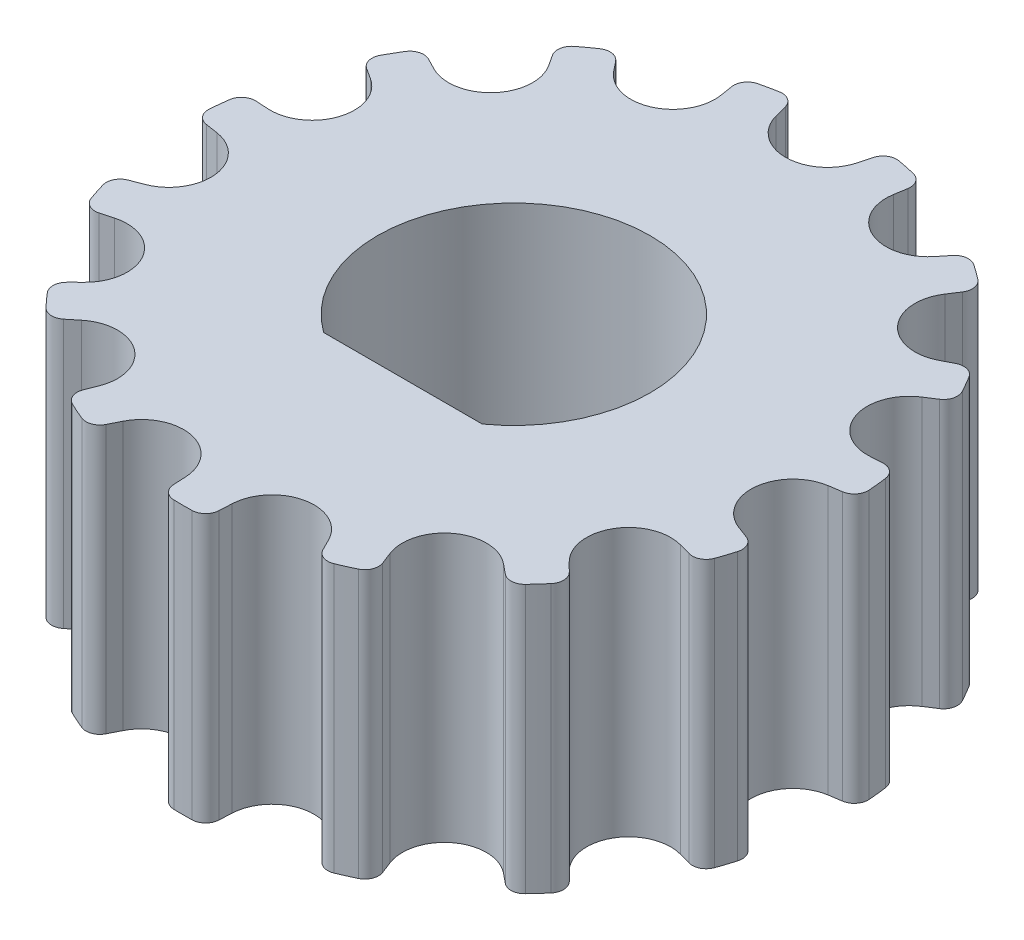
SolidWorks part; units mm, degrees
material "Acrylic (Medium-high impact)"
ref_plane "Front Plane" through (0, 0, 0) normal (0, 0, 1) x (1, 0, 0)
ref_plane "Top Plane" through (0, 0, 0) normal (0, 1, 0) x (1, 0, 0)
ref_plane "Right Plane" through (0, 0, 0) normal (1, 0, 0) x (0, 0, -1)
sketch "Sketch1" plane through (0, 0, 0) normal (0, 1, 0) x (1, 0, 0)
  circle A0 centre (0, 0) radius 7.162
  dimension "D1" = 14.3239
extrude "Boss-Extrude1" add sketch "Sketch1" along normal blind 5.8
sketch "Sketch2" plane through (0, 5.8, 0) normal (0, 1, 0) x (1, 0, 0)
  line L0 (0, 0) -> (0, 7.162) construction
  line L1 (-0.8799, 6.5598) -> (-0.95, 6.8255)
  line L2 (-2.913, 6.5428) -> (-2.913, 7.162)
  line L3 (-2.913, 7.162) -> (2.913, 7.162)
  line L4 (0.8799, 6.5598) -> (0.95, 6.8255)
  line L5 (2.913, 6.5428) -> (2.913, 7.162)
  circle A0 centre (0, 0) radius 7.162 construction
  arc A1 (0.8799, 6.5598) -> (-0.8799, 6.5598) centre (0, 6.792) cw
  arc A2 (-0.95, 6.8255) -> (-1.2943, 7.0441) centre (-1.2401, 6.749) ccw
  arc A4 (0.95, 6.8255) -> (1.2943, 7.0441) centre (1.2401, 6.749) cw
  arc A5 (-1.2943, 7.0441) -> (-2.913, 6.5428) centre (0, 0) ccw
  arc A6 (1.2943, 7.0441) -> (2.913, 6.5428) centre (0, 0) cw
  point P11 (0, 7.162)
  point P19 (0, 5.882)
  dimension "D3" = 0.3
  dimension "D5" = 0.91
  dimension "D2" = 0.95
  dimension "D4" = 1.28
  dimension "D6" = 24
extrude "Cut-Extrude1" cut sketch "Sketch2" against normal through all
pattern_circular "CirPattern1" count 15 over 360 about axis through (0, 0, 0) along (0, 1, 0) of "Cut-Extrude1"
sketch "Sketch3" plane through (0, 0, 0) normal (0, -1, 0) x (1, 0, 0)
  line L0 (1.7154, 2.4) -> (-1.7154, 2.4)
  arc A0 (-1.7154, 2.4) -> (1.7154, 2.4) centre (0, 0) ccw
  dimension "D1" = 5.9
  dimension "D2" = 2.4
extrude "Cut-Extrude2" cut sketch "Sketch3" against normal through all
sketch "Sketch5" plane through (0, 0, 0) normal (0, -1, 0) x (1, 0, 0)
  line L60 (5.4179, -3.8244) -> (5.6623, -3.9501)
  line L61 (6.252, -2.9286) -> (6.021, -2.7798)
  line L62 (6.505, -1.2901) -> (6.7794, -1.3055)
  line L63 (6.9027, -0.1325) -> (6.6311, -0.0906)
  line L64 (6.4674, 1.4673) -> (6.7243, 1.5648)
  line L65 (6.3598, 2.6865) -> (6.0946, 2.6144)
  line L66 (5.3115, 3.9709) -> (5.5065, 4.1645)
  line L67 (4.7173, 5.041) -> (4.5044, 4.8673)
  line L68 (3.2371, 5.788) -> (3.3366, 6.0442)
  line L69 (2.2591, 6.5239) -> (2.1352, 6.2786)
  line L70 (0.6031, 6.6042) -> (0.5897, 6.8787)
  line L71 (-0.5897, 6.8787) -> (-0.6031, 6.6042)
  line L72 (-2.1352, 6.2786) -> (-2.2591, 6.5239)
  line L73 (-3.3366, 6.0442) -> (-3.2371, 5.788)
  line L74 (-4.5044, 4.8673) -> (-4.7173, 5.041)
  line L75 (-5.5065, 4.1645) -> (-5.3115, 3.9709)
  line L76 (-6.0946, 2.6144) -> (-6.3598, 2.6865)
  line L77 (-6.7243, 1.5648) -> (-6.4674, 1.4673)
  line L78 (-6.6311, -0.0906) -> (-6.9027, -0.1325)
  line L79 (-6.7794, -1.3055) -> (-6.505, -1.2901)
  line L80 (-6.021, -2.7798) -> (-6.252, -2.9286)
  line L81 (-5.6623, -3.9501) -> (-5.4179, -3.8244)
  line L82 (-4.3698, -4.9885) -> (-4.5203, -5.2184)
  line L83 (-3.5661, -5.9117) -> (-3.394, -5.6974)
  line L84 (-1.963, -6.3345) -> (-2.007, -6.6058)
  line L85 (-0.8533, -6.851) -> (-0.7832, -6.5853)
  line L86 (0.7832, -6.5853) -> (0.8533, -6.851)
  line L87 (2.007, -6.6058) -> (1.963, -6.3345)
  line L88 (3.394, -5.6974) -> (3.5661, -5.9117)
  line L89 (4.5203, -5.2184) -> (4.3698, -4.9885)
  line L90 (5.4179, -3.8244) -> (5.6623, -3.9501)
  line L91 (6.252, -2.9286) -> (6.021, -2.7798)
  line L92 (6.505, -1.2901) -> (6.7794, -1.3055)
  line L93 (6.9027, -0.1325) -> (6.6311, -0.0906)
  line L94 (6.4674, 1.4673) -> (6.7243, 1.5648)
  line L95 (6.3598, 2.6865) -> (6.0946, 2.6144)
  line L96 (5.3115, 3.9709) -> (5.5065, 4.1645)
  line L97 (4.7173, 5.041) -> (4.5044, 4.8673)
  line L98 (3.2371, 5.788) -> (3.3366, 6.0442)
  line L99 (2.2591, 6.5239) -> (2.1352, 6.2786)
  line L100 (0.6031, 6.6042) -> (0.5897, 6.8787)
  line L101 (-0.5897, 6.8787) -> (-0.6031, 6.6042)
  line L102 (-2.1352, 6.2786) -> (-2.2591, 6.5239)
  line L103 (-3.3366, 6.0442) -> (-3.2371, 5.788)
  line L104 (-4.5044, 4.8673) -> (-4.7173, 5.041)
  line L105 (-5.5065, 4.1645) -> (-5.3115, 3.9709)
  line L106 (-6.0946, 2.6144) -> (-6.3598, 2.6865)
  line L107 (-6.7243, 1.5648) -> (-6.4674, 1.4673)
  line L108 (-6.6311, -0.0906) -> (-6.9027, -0.1325)
  line L109 (-6.7794, -1.3055) -> (-6.505, -1.2901)
  line L110 (-6.021, -2.7798) -> (-6.252, -2.9286)
  line L111 (-5.6623, -3.9501) -> (-5.4179, -3.8244)
  line L112 (-4.3698, -4.9885) -> (-4.5203, -5.2184)
  line L113 (-3.5661, -5.9117) -> (-3.394, -5.6974)
  line L114 (-1.963, -6.3345) -> (-2.007, -6.6058)
  line L115 (-0.8533, -6.851) -> (-0.7832, -6.5853)
  line L116 (0.7832, -6.5853) -> (0.8533, -6.851)
  line L117 (2.007, -6.6058) -> (1.963, -6.3345)
  line L118 (3.394, -5.6974) -> (3.5661, -5.9117)
  line L119 (4.5203, -5.2184) -> (4.3698, -4.9885)
  circle A60 centre (0, 0) radius 3.9038
  arc A120 (5.6623, -3.9501) -> (6.186, -3.8039) centre (5.8452, -3.5944) ccw
  arc A121 (6.186, -3.8039) -> (6.3873, -3.4553) centre (0, 0) ccw
  arc A122 (6.3873, -3.4553) -> (6.252, -2.9286) centre (6.0355, -3.2649) ccw
  arc A123 (6.505, -1.2901) -> (6.021, -2.7798) centre (6.4595, -2.0988) ccw
  arc A124 (6.7794, -1.3055) -> (7.1984, -0.959) centre (6.8019, -0.9062) ccw
  arc A125 (7.1984, -0.959) -> (7.2405, -0.5586) centre (0, 0) ccw
  arc A126 (7.2405, -0.5586) -> (6.9027, -0.1325) centre (6.8416, -0.5278) ccw
  arc A127 (6.4674, 1.4673) -> (6.6311, -0.0906) centre (6.7548, 0.71) ccw
  arc A128 (6.7243, 1.5648) -> (6.9661, 2.0518) centre (6.5824, 1.9387) ccw
  arc A129 (6.9661, 2.0518) -> (6.8417, 2.4347) centre (0, 0) ccw
  arc A130 (6.8417, 2.4347) -> (6.3598, 2.6865) centre (6.4648, 2.3006) ccw
  arc A131 (5.3115, 3.9709) -> (6.0946, 2.6144) centre (5.882, 3.396) ccw
  arc A132 (5.5065, 4.1645) -> (5.5293, 4.7077) centre (5.2248, 4.4484) ccw
  arc A133 (5.5293, 4.7077) -> (5.2599, 5.0069) centre (0, 0) ccw
  arc A134 (5.2599, 5.0069) -> (4.7173, 5.041) centre (4.9702, 4.7312) ccw
  arc A135 (3.2371, 5.788) -> (4.5044, 4.8673) centre (3.9922, 5.4948) ccw
  arc A136 (3.3366, 6.0442) -> (3.1365, 6.5497) centre (2.9637, 6.1889) ccw
  arc A137 (3.1365, 6.5497) -> (2.7687, 6.7135) centre (0, 0) ccw
  arc A138 (2.7687, 6.7135) -> (2.2591, 6.5239) centre (2.6162, 6.3437) ccw
  arc A139 (0.6031, 6.6042) -> (2.1352, 6.2786) centre (1.4121, 6.6436) ccw
  arc A140 (0.5897, 6.8787) -> (0.2013, 7.2592) centre (0.1902, 6.8593) ccw
  arc A141 (0.2013, 7.2592) -> (-0.2013, 7.2592) centre (0, 0) ccw
  arc A142 (-0.2013, 7.2592) -> (-0.5897, 6.8787) centre (-0.1902, 6.8593) ccw
  arc A143 (-2.1352, 6.2786) -> (-0.6031, 6.6042) centre (-1.4121, 6.6436) ccw
  arc A144 (-2.2591, 6.5239) -> (-2.7687, 6.7135) centre (-2.6162, 6.3437) ccw
  arc A145 (-2.7687, 6.7135) -> (-3.1365, 6.5497) centre (0, 0) ccw
  arc A146 (-3.1365, 6.5497) -> (-3.3366, 6.0442) centre (-2.9637, 6.1889) ccw
  arc A147 (-4.5044, 4.8673) -> (-3.2371, 5.788) centre (-3.9922, 5.4948) ccw
  arc A148 (-4.7173, 5.041) -> (-5.2599, 5.0069) centre (-4.9702, 4.7312) ccw
  arc A149 (-5.2599, 5.0069) -> (-5.5293, 4.7077) centre (0, 0) ccw
  arc A150 (-5.5293, 4.7077) -> (-5.5065, 4.1645) centre (-5.2248, 4.4484) ccw
  arc A151 (-6.0946, 2.6144) -> (-5.3115, 3.9709) centre (-5.882, 3.396) ccw
  arc A152 (-6.3598, 2.6865) -> (-6.8417, 2.4347) centre (-6.4648, 2.3006) ccw
  arc A153 (-6.8417, 2.4347) -> (-6.9661, 2.0518) centre (0, 0) ccw
  arc A154 (-6.9661, 2.0518) -> (-6.7243, 1.5648) centre (-6.5824, 1.9387) ccw
  arc A155 (-6.6311, -0.0906) -> (-6.4674, 1.4673) centre (-6.7548, 0.71) ccw
  arc A156 (-6.9027, -0.1325) -> (-7.2405, -0.5586) centre (-6.8416, -0.5278) ccw
  arc A157 (-7.2405, -0.5586) -> (-7.1984, -0.959) centre (0, 0) ccw
  arc A158 (-7.1984, -0.959) -> (-6.7794, -1.3055) centre (-6.8019, -0.9062) ccw
  arc A159 (-6.021, -2.7798) -> (-6.505, -1.2901) centre (-6.4595, -2.0988) ccw
  arc A160 (-6.252, -2.9286) -> (-6.3873, -3.4553) centre (-6.0355, -3.2649) ccw
  arc A161 (-6.3873, -3.4553) -> (-6.186, -3.8039) centre (0, 0) ccw
  arc A162 (-6.186, -3.8039) -> (-5.6623, -3.9501) centre (-5.8452, -3.5944) ccw
  arc A163 (-4.3698, -4.9885) -> (-5.4179, -3.8244) centre (-5.0474, -4.5447) ccw
  arc A164 (-4.5203, -5.2184) -> (-4.4297, -5.7545) centre (-4.1857, -5.4375) ccw
  arc A165 (-4.4297, -5.7545) -> (-4.104, -5.9911) centre (0, 0) ccw
  arc A166 (-4.104, -5.9911) -> (-3.5661, -5.9117) centre (-3.8779, -5.6611) ccw
  arc A167 (-1.963, -6.3345) -> (-3.394, -5.6974) centre (-2.7625, -6.2048) ccw
  arc A168 (-2.007, -6.6058) -> (-1.7062, -7.0587) centre (-1.6122, -6.6699) ccw
  arc A169 (-1.7062, -7.0587) -> (-1.3124, -7.1424) centre (0, 0) ccw
  arc A170 (-1.3124, -7.1424) -> (-0.8533, -6.851) centre (-1.2401, -6.749) ccw
  arc A171 (0.7832, -6.5853) -> (-0.7832, -6.5853) centre (0, -6.792) ccw
  arc A172 (0.8533, -6.851) -> (1.3124, -7.1424) centre (1.2401, -6.749) ccw
  arc A173 (1.3124, -7.1424) -> (1.7062, -7.0587) centre (0, 0) ccw
  arc A174 (1.7062, -7.0587) -> (2.007, -6.6058) centre (1.6122, -6.6699) ccw
  arc A175 (3.394, -5.6974) -> (1.963, -6.3345) centre (2.7625, -6.2048) ccw
  arc A176 (3.5661, -5.9117) -> (4.104, -5.9911) centre (3.8779, -5.6611) ccw
  arc A177 (4.104, -5.9911) -> (4.4297, -5.7545) centre (0, 0) ccw
  arc A178 (4.4297, -5.7545) -> (4.5203, -5.2184) centre (4.1857, -5.4375) ccw
  arc A179 (5.4179, -3.8244) -> (4.3698, -4.9885) centre (5.0474, -4.5447) ccw
  arc A180 (5.6623, -3.9501) -> (6.186, -3.8039) centre (5.8452, -3.5944) ccw
  arc A181 (6.186, -3.8039) -> (6.3873, -3.4553) centre (0, 0) ccw
  arc A182 (6.3873, -3.4553) -> (6.252, -2.9286) centre (6.0355, -3.2649) ccw
  arc A183 (6.505, -1.2901) -> (6.021, -2.7798) centre (6.4595, -2.0988) ccw
  arc A184 (6.7794, -1.3055) -> (7.1984, -0.959) centre (6.8019, -0.9062) ccw
  arc A185 (7.1984, -0.959) -> (7.2405, -0.5586) centre (0, 0) ccw
  arc A186 (7.2405, -0.5586) -> (6.9027, -0.1325) centre (6.8416, -0.5278) ccw
  arc A187 (6.4674, 1.4673) -> (6.6311, -0.0906) centre (6.7548, 0.71) ccw
  arc A188 (6.7243, 1.5648) -> (6.9661, 2.0518) centre (6.5824, 1.9387) ccw
  arc A189 (6.9661, 2.0518) -> (6.8417, 2.4347) centre (0, 0) ccw
  arc A190 (6.8417, 2.4347) -> (6.3598, 2.6865) centre (6.4648, 2.3006) ccw
  arc A191 (5.3115, 3.9709) -> (6.0946, 2.6144) centre (5.882, 3.396) ccw
  arc A192 (5.5065, 4.1645) -> (5.5293, 4.7077) centre (5.2248, 4.4484) ccw
  arc A193 (5.5293, 4.7077) -> (5.2599, 5.0069) centre (0, 0) ccw
  arc A194 (5.2599, 5.0069) -> (4.7173, 5.041) centre (4.9702, 4.7312) ccw
  arc A195 (3.2371, 5.788) -> (4.5044, 4.8673) centre (3.9922, 5.4948) ccw
  arc A196 (3.3366, 6.0442) -> (3.1365, 6.5497) centre (2.9637, 6.1889) ccw
  arc A197 (3.1365, 6.5497) -> (2.7687, 6.7135) centre (0, 0) ccw
  arc A198 (2.7687, 6.7135) -> (2.2591, 6.5239) centre (2.6162, 6.3437) ccw
  arc A199 (0.6031, 6.6042) -> (2.1352, 6.2786) centre (1.4121, 6.6436) ccw
  arc A200 (0.5897, 6.8787) -> (0.2013, 7.2592) centre (0.1902, 6.8593) ccw
  arc A201 (0.2013, 7.2592) -> (-0.2013, 7.2592) centre (0, 0) ccw
  arc A202 (-0.2013, 7.2592) -> (-0.5897, 6.8787) centre (-0.1902, 6.8593) ccw
  arc A203 (-2.1352, 6.2786) -> (-0.6031, 6.6042) centre (-1.4121, 6.6436) ccw
  arc A204 (-2.2591, 6.5239) -> (-2.7687, 6.7135) centre (-2.6162, 6.3437) ccw
  arc A205 (-2.7687, 6.7135) -> (-3.1365, 6.5497) centre (0, 0) ccw
  arc A206 (-3.1365, 6.5497) -> (-3.3366, 6.0442) centre (-2.9637, 6.1889) ccw
  arc A207 (-4.5044, 4.8673) -> (-3.2371, 5.788) centre (-3.9922, 5.4948) ccw
  arc A208 (-4.7173, 5.041) -> (-5.2599, 5.0069) centre (-4.9702, 4.7312) ccw
  arc A209 (-5.2599, 5.0069) -> (-5.5293, 4.7077) centre (0, 0) ccw
  arc A210 (-5.5293, 4.7077) -> (-5.5065, 4.1645) centre (-5.2248, 4.4484) ccw
  arc A211 (-6.0946, 2.6144) -> (-5.3115, 3.9709) centre (-5.882, 3.396) ccw
  arc A212 (-6.3598, 2.6865) -> (-6.8417, 2.4347) centre (-6.4648, 2.3006) ccw
  arc A213 (-6.8417, 2.4347) -> (-6.9661, 2.0518) centre (0, 0) ccw
  arc A214 (-6.9661, 2.0518) -> (-6.7243, 1.5648) centre (-6.5824, 1.9387) ccw
  arc A215 (-6.6311, -0.0906) -> (-6.4674, 1.4673) centre (-6.7548, 0.71) ccw
  arc A216 (-6.9027, -0.1325) -> (-7.2405, -0.5586) centre (-6.8416, -0.5278) ccw
  arc A217 (-7.2405, -0.5586) -> (-7.1984, -0.959) centre (0, 0) ccw
  arc A218 (-7.1984, -0.959) -> (-6.7794, -1.3055) centre (-6.8019, -0.9062) ccw
  arc A219 (-6.021, -2.7798) -> (-6.505, -1.2901) centre (-6.4595, -2.0988) ccw
  arc A220 (-6.252, -2.9286) -> (-6.3873, -3.4553) centre (-6.0355, -3.2649) ccw
  arc A221 (-6.3873, -3.4553) -> (-6.186, -3.8039) centre (0, 0) ccw
  arc A222 (-6.186, -3.8039) -> (-5.6623, -3.9501) centre (-5.8452, -3.5944) ccw
  arc A223 (-4.3698, -4.9885) -> (-5.4179, -3.8244) centre (-5.0474, -4.5447) ccw
  arc A224 (-4.5203, -5.2184) -> (-4.4297, -5.7545) centre (-4.1857, -5.4375) ccw
  arc A225 (-4.4297, -5.7545) -> (-4.104, -5.9911) centre (0, 0) ccw
  arc A226 (-4.104, -5.9911) -> (-3.5661, -5.9117) centre (-3.8779, -5.6611) ccw
  arc A227 (-1.963, -6.3345) -> (-3.394, -5.6974) centre (-2.7625, -6.2048) ccw
  arc A228 (-2.007, -6.6058) -> (-1.7062, -7.0587) centre (-1.6122, -6.6699) ccw
  arc A229 (-1.7062, -7.0587) -> (-1.3124, -7.1424) centre (0, 0) ccw
  arc A230 (-1.3124, -7.1424) -> (-0.8533, -6.851) centre (-1.2401, -6.749) ccw
  arc A231 (0.7832, -6.5853) -> (-0.7832, -6.5853) centre (0, -6.792) ccw
  arc A232 (0.8533, -6.851) -> (1.3124, -7.1424) centre (1.2401, -6.749) ccw
  arc A233 (1.3124, -7.1424) -> (1.7062, -7.0587) centre (0, 0) ccw
  arc A234 (1.7062, -7.0587) -> (2.007, -6.6058) centre (1.6122, -6.6699) ccw
  arc A235 (3.394, -5.6974) -> (1.963, -6.3345) centre (2.7625, -6.2048) ccw
  arc A236 (3.5661, -5.9117) -> (4.104, -5.9911) centre (3.8779, -5.6611) ccw
  arc A237 (4.104, -5.9911) -> (4.4297, -5.7545) centre (0, 0) ccw
  arc A238 (4.4297, -5.7545) -> (4.5203, -5.2184) centre (4.1857, -5.4375) ccw
  arc A239 (5.4179, -3.8244) -> (4.3698, -4.9885) centre (5.0474, -4.5447) ccw
  dimension "D1" = 0.1
extrude "Boss-Extrude2" [suppressed] add sketch "Sketch5" against normal up to surface (5.8 mm away)
sketch "Sketch6" plane through (0, 5.8, 0) normal (0, 1, 0) x (1, 0, 0)
  circle A0 centre (0, -10) radius 2.5
  dimension "D1" = 5
  dimension "D2" = 10
extrude "Cut-Extrude3" [suppressed] cut sketch "Sketch6" against normal through all
equation "\"smallPulleyTeeth\"= 15"
equation "\"largePulleyTeeth\"= 30"
equation "\"eighthThick\"= 2.9mm"
equation "\"D1@Sketch1\"=3*\"smallPulleyTeeth\"/pi"
equation "\"D1@Boss-Extrude1\" = \"eighthThick\" * 2"
equation "\"D6@Sketch2\"=360/\"smallPulleyTeeth\""
equation "\"quarterThick\"=6.0mm"
equation "\"D1@CirPattern1\"=\"smallPulleyTeeth\""
equation "\"sixteenthThick\"= 1.7mm"
equation "\"OD\"= 145mm"
equation "\"puckAngle\"= 60.5deg"
equation "\"puckDiam\"= 76.5mm"
equation "\"axlePress\"= 5.9mm"
equation "\"press\"= 0.2mm"
equation "\"wheelClear\"= 0.3mm"
equation "\"10-32clear\"= 4.8mm"
equation "\"6-32clear\"= 3.3mm"
equation "\"8-32clear\"= 4.0mm"
equation "\"wheelHeight\"= 22mm"
equation "\"D1@Sketch3\"=\"axlePress\""
